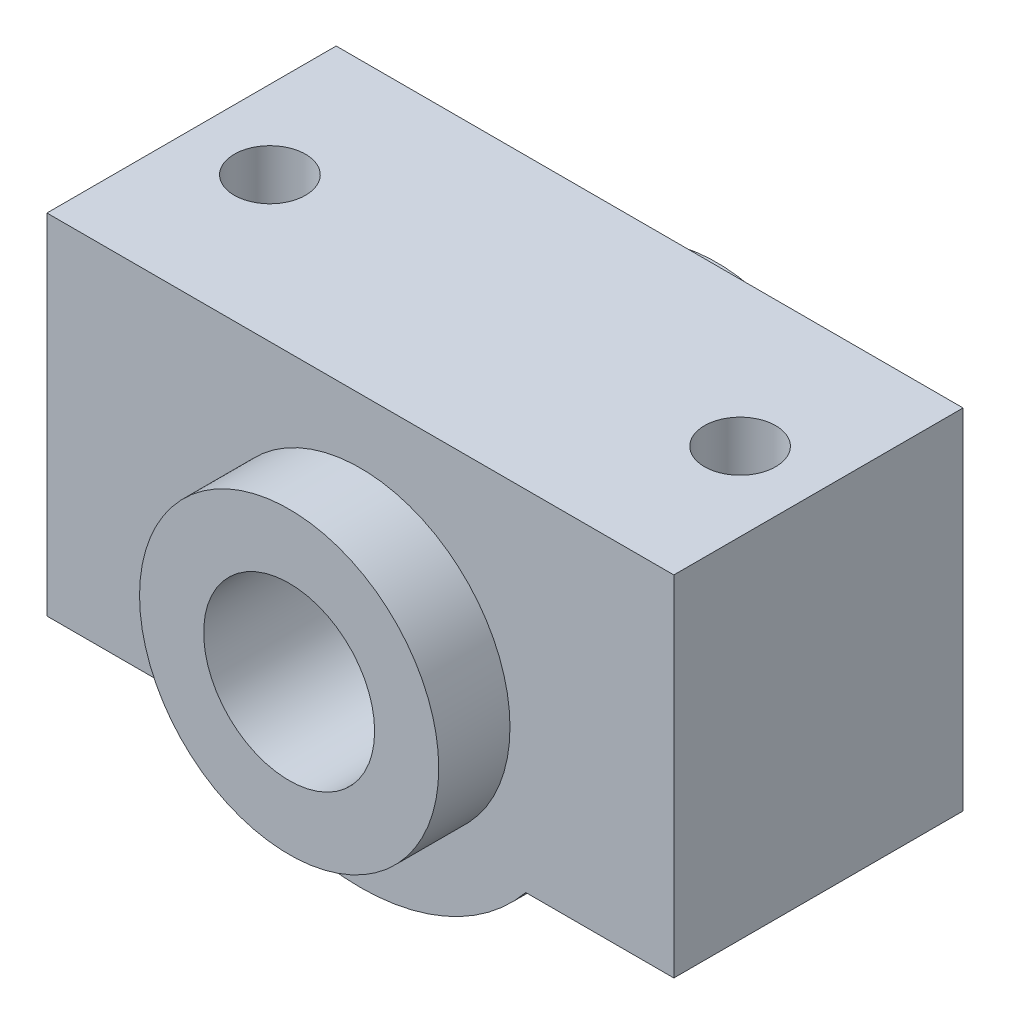
SolidWorks part; units mm, degrees
ref_plane "Ön Düzlem" through (0, 0, 0) normal (0, 0, 1) x (1, 0, 0)
ref_plane "Üst Düzlem" through (0, 0, 0) normal (0, 1, 0) x (1, 0, 0)
ref_plane "Sağ Düzlem" through (0, 0, 0) normal (1, 0, 0) x (0, 0, -1)
sketch "Çizim1" plane through (0, 0, 0) normal (0, 0, 1) x (1, 0, 0)
  line L0 (-22, -9.5) -> (-11.6082, -9.5)
  line L1 (-22, 15) -> (22, 15)
  line L2 (-22, 15) -> (-22, -9.5)
  line L4 (22, 15) -> (22, -9.5)
  line L5 (-22, 15) -> (13.9333, -9.5) construction
  line L6 (-22, -15) -> (22, 15) construction
  line L7 (11.6082, -9.5) -> (22, -9.5)
  circle A1 centre (0, 0) radius 6
  arc A2 (-11.6082, -9.5) -> (11.6082, -9.5) centre (0, 0) ccw
  point P0 (0, 0)
  dimension "D3" = 12
  dimension "D4" = 24.5
  dimension "D1" = 44
  dimension "D2" = 30
extrude "Yükseklik-Ekstrüzyon1" add sketch "Çizim1" along normal blind 20.3
sketch "Çizim2" plane through (0, 0, 20.3) normal (0, 0, 1) x (1, 0, 0)
  circle A0 centre (0, 0) radius 10.5
  circle A1 centre (0, 0) radius 6
  dimension "D1" = 21
  dimension "D2" = 12
extrude "Yükseklik-Ekstrüzyon2" add sketch "Çizim2" along normal blind 5 and the other way blind 25
sketch "Çizim5" plane through (0, 15, 0) normal (0, 1, 0) x (1, 0, 0)
  line L0 (22, 0) -> (-22, 0) construction
  circle A0 centre (-16.5, -10.15) radius 2.5
  circle A1 centre (16.5, -10.15) radius 2.5
  point P4 (0, 0)
  point P5 (0, 0)
  point P6 (0, 0)
  point P7 (0, 0)
  point P8 (0, 0)
  point P9 (2.0019, -12.3717)
  point P13 (0, 0)
  dimension "D1" = 5
  dimension "D2" = 5
  dimension "D3" = 33
  dimension "D4" = 16.5
  dimension "D5" = 10.15
extrude "Kes-Ekstrüzyon1" cut sketch "Çizim5" against normal through all
